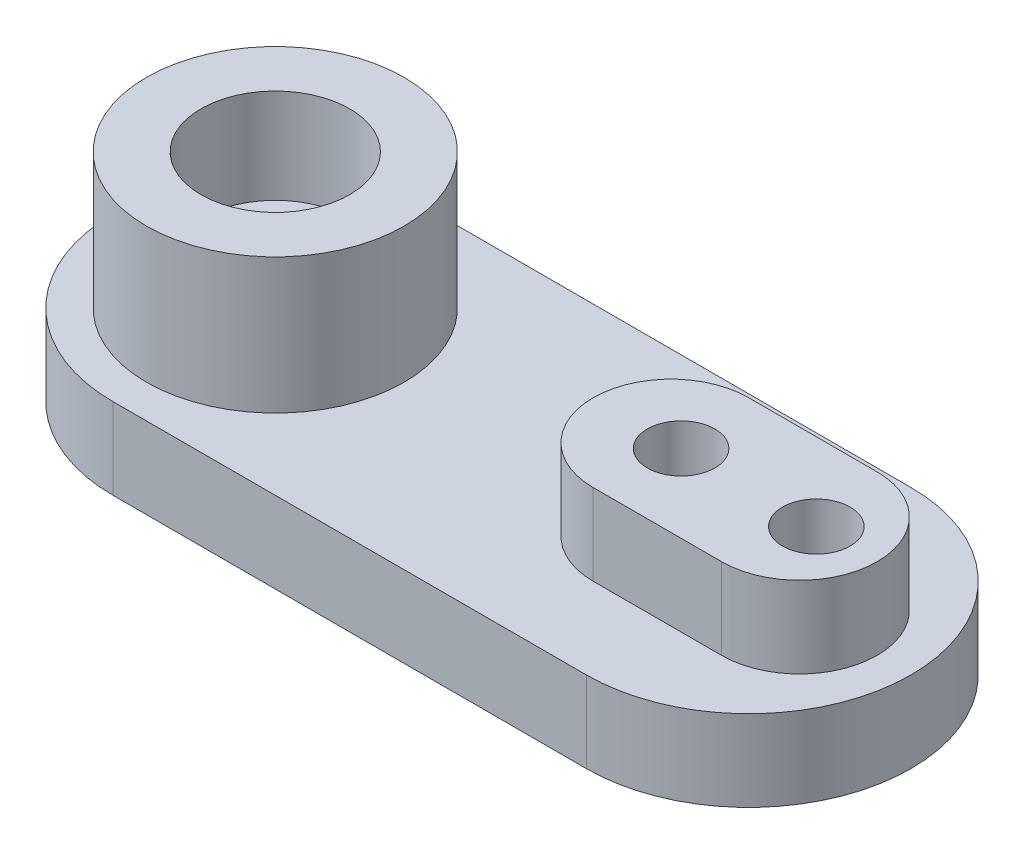
SolidWorks part; units mm, degrees
ref_plane "Front Plane" through (0, 0, 0) normal (0, 0, 1) x (1, 0, 0)
ref_plane "Top Plane" through (0, 0, 0) normal (0, 1, 0) x (1, 0, 0)
ref_plane "Right Plane" through (0, 0, 0) normal (1, 0, 0) x (0, 0, -1)
sketch "Sketch1" plane through (0, 0, 0) normal (0, 1, 0) x (1, 0, 0)
  line L0 (0, 0) -> (17.5, 0) construction
  line L1 (0, 6) -> (17.5, 6)
  line L2 (0, -6) -> (17.5, -6)
  arc A0 (0, 6) -> (0, -6) centre (0, 0) ccw
  arc A1 (17.5, -6) -> (17.5, 6) centre (17.5, 0) ccw
  point P3 (8.75, 0)
  dimension "D1" = 6
  dimension "D2" = 17.5
extrude "Boss-Extrude1" add sketch "Sketch1" along normal blind 3
sketch "Sketch2" plane through (0, 3, 0) normal (0, 1, 0) x (1, 0, 0)
  circle A0 centre (0, 0) radius 4.7625
  dimension "D1" = 9.525
extrude "Boss-Extrude2" add sketch "Sketch2" along normal blind 5
sketch "Sketch3" plane through (0, 3, 0) normal (0, 1, 0) x (1, 0, 0)
  line L0 (19.375, 0) -> (14.625, 0) construction
  line L1 (19.375, -2.875) -> (14.625, -2.875)
  line L2 (19.375, 2.875) -> (14.625, 2.875)
  line L3 (11.75, 0) -> (22.25, 0) construction
  arc A0 (19.375, -2.875) -> (19.375, 2.875) centre (19.375, 0) ccw
  arc A1 (14.625, 2.875) -> (14.625, -2.875) centre (14.625, 0) ccw
  arc A2 (17.5, -6) -> (17.5, 6) centre (17.5, 0) ccw construction
  point P3 (17, 0)
  point P10 (23.5, 0)
  dimension "D1" = 2.875
  dimension "D2" = 10.5
  dimension "D3" = 1.25
extrude "Boss-Extrude3" add sketch "Sketch3" along normal blind 3
sketch "Sketch4" plane through (0, 8, 0) normal (0, 1, 0) x (1, 0, 0)
  circle A0 centre (0, 0) radius 2.75
  dimension "D1" = 5.5
extrude "Cut-Extrude1" cut sketch "Sketch4" against normal blind 3.5
sketch "Sketch5" plane through (0, 6, 0) normal (0, 1, 0) x (1, 0, 0)
  line L0 (11.75, 0) -> (22.25, 0) construction
  line L1 (21.25, 0) -> (22.25, 0) construction
  line L2 (18.75, 0) -> (16.25, 0) construction
  arc A0 (14.625, 2.875) -> (14.625, -2.875) centre (14.625, 0) ccw construction
  arc A1 (19.375, -2.875) -> (19.375, 2.875) centre (19.375, 0) ccw construction
  circle A2 centre (20, 0) radius 1.25
  circle A3 centre (15, 0) radius 1.25
  dimension "D1" = 2.5
  dimension "D2" = 1
  dimension "D3" = 2.5
extrude "Cut-Extrude2" cut sketch "Sketch5" against normal through all
sketch "Sketch6" plane through (0, 4.5, 0) normal (0, 1, 0) x (1, 0, 0)
  circle A0 centre (0, 0) radius 1.75
  dimension "D1" = 3.5
extrude "Cut-Extrude3" cut sketch "Sketch6" against normal through all
sketch "Sketch7" plane through (0, 0, 0) normal (0, -1, 0) x (1, 0, 0)
  circle A0 centre (0, 0) radius 3
  dimension "D1" = 6
extrude "Cut-Extrude4" cut sketch "Sketch7" against normal blind 2.5
